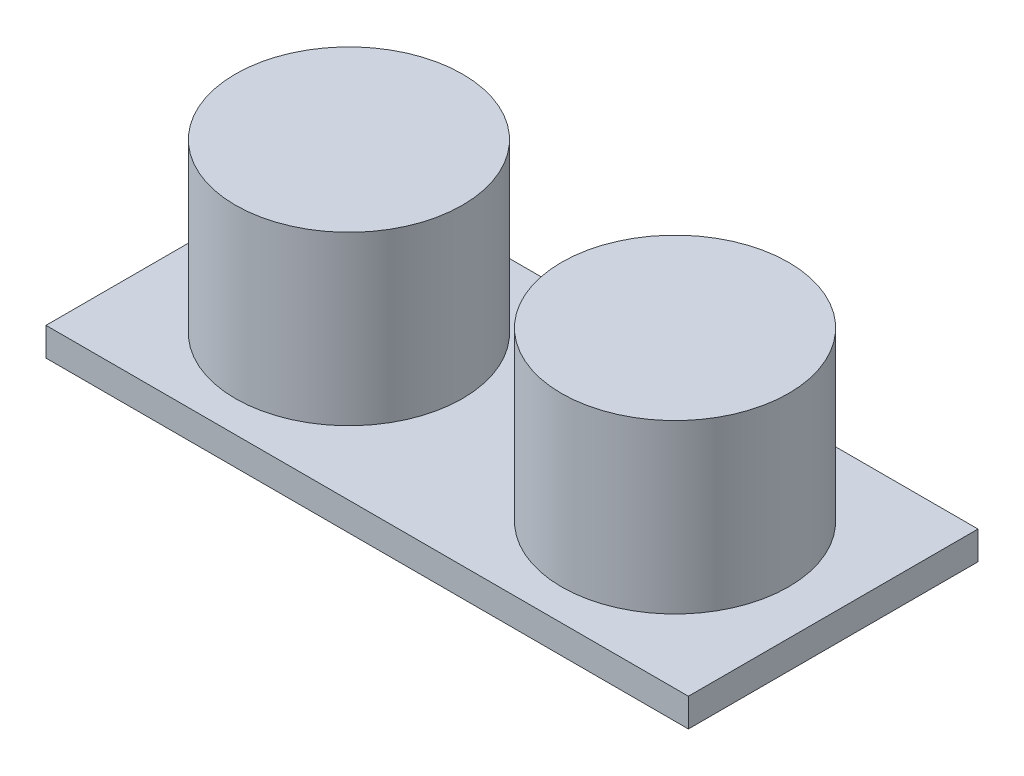
SolidWorks part; units mm, degrees
ref_plane "Alzado" through (0, 0, 0) normal (0, 0, 1) x (1, 0, 0)
ref_plane "Planta" through (0, 0, 0) normal (0, 1, 0) x (1, 0, 0)
ref_plane "Vista lateral" through (0, 0, 0) normal (1, 0, 0) x (0, 0, -1)
sketch "Croquis1" plane through (0, 0, 0) normal (0, 1, 0) x (1, 0, 0)
  line L0 (-21.3608, -12.3352) -> (-18.2221, -12.3352) construction
  line L1 (-21.3608, 8.0648) -> (23.8892, 8.0648)
  line L2 (-21.3608, 8.0648) -> (-21.3608, -12.3352)
  line L3 (-21.3608, -12.3352) -> (23.8892, -12.3352)
  line L4 (23.8892, 8.0648) -> (23.8892, -12.3352)
  line L5 (23.8892, -12.3352) -> (20.7492, -12.3352) construction
  line L6 (-18.2221, -12.3352) -> (-10.2221, -12.3352) construction
  line L7 (-10.2221, -12.3352) -> (-10.2221, 8.0648) construction
  line L8 (20.7492, -12.3352) -> (12.7492, -12.3352) construction
  line L9 (12.7492, -12.3352) -> (12.7492, 8.0648) construction
  circle A0 centre (-10.2221, -2.1352) radius 8
  circle A1 centre (12.7492, -2.1352) radius 8
  dimension "D1" = 45.25
  dimension "D2" = 20.4
  dimension "D3" = 3.1387
  dimension "D4" = 3.14
extrude "Saliente-Extruir1" add sketch "Croquis1" along normal blind 2
sketch "Croquis2" plane through (0, 0, 0) normal (0, -1, 0) x (-1, 0, 0)
  line L0 (18.2221, -2.1352) -> (2.2221, -2.1352) construction
  line L1 (-4.7492, -2.1352) -> (-20.7492, -2.1352) construction
  circle A0 centre (10.2221, -2.1352) radius 8 construction
  circle A1 centre (-12.7492, -2.1352) radius 8 construction
  circle A2 centre (10.2221, -2.1352) radius 8
  circle A3 centre (-12.7492, -2.1352) radius 8
extrude "Saliente-Extruir2" add sketch "Croquis2" against normal blind 13.8
sketch "Croquis3" plane through (0, 0, 0) normal (0, -1, 0) x (-1, 0, 0)
  line L0 (-23.8892, 8.0648) -> (-6.4892, 8.0648)
  line L1 (-23.8892, 8.0648) -> (21.3608, 8.0648) construction
  line L2 (21.3608, 8.0648) -> (3.9608, 8.0648)
  line L4 (-6.4892, 8.0648) -> (3.9608, 8.0648)
  line L5 (-6.4892, 8.0648) -> (-6.4892, 5.5648)
  line L6 (-6.4892, 5.5648) -> (3.9608, 5.5648)
  line L7 (3.9608, 8.0648) -> (3.9608, 5.5648)
  line M5 (21.3608, 8.0648) -> (-23.8892, 8.0648)
  dimension "D1" = 17.4
  dimension "D2" = 17.4
  dimension "D3" = 2.5
extrude "Saliente-Extruir4" add sketch "Croquis3" along normal blind 4.3 contours L7 L5 L6 M5
sketch "Croquis4" plane through (0, 0, -8.0648) normal (0, 0, -1) x (-1, 0, 0)
  line L0 (3.9608, -4.3) -> (3.9608, 0) construction
  line L1 (-6.4892, -4.3) -> (3.9608, -4.3)
  line L2 (-6.4892, -4.3) -> (-6.4892, -2.3)
  line L3 (-6.4892, -2.3) -> (3.9608, -2.3)
  line L4 (3.9608, -4.3) -> (3.9608, -2.3)
  dimension "D1" = 2
extrude "Saliente-Extruir5" add sketch "Croquis4" along normal blind 6.4
